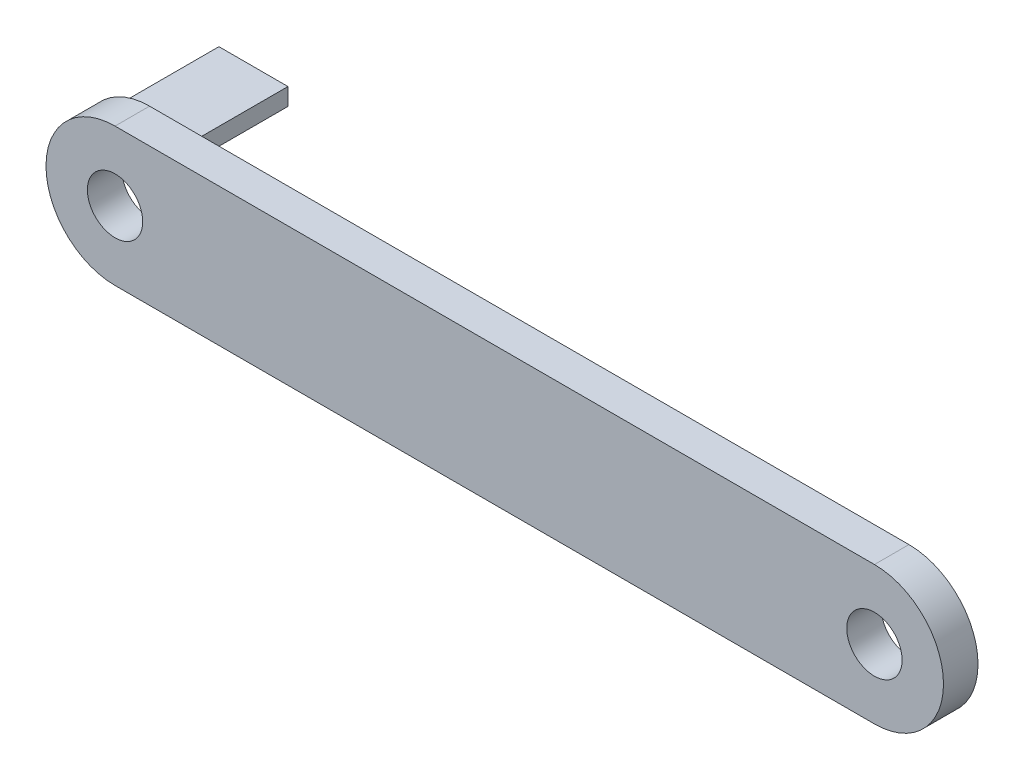
SolidWorks part; units mm, degrees
ref_plane "Front Plane" through (0, 0, 0) normal (0, 0, 1) x (1, 0, 0)
ref_plane "Top Plane" through (0, 0, 0) normal (0, 1, 0) x (1, 0, 0)
ref_plane "Right Plane" through (0, 0, 0) normal (1, 0, 0) x (0, 0, -1)
sketch "Sketch1" plane through (0, 0, 0) normal (0, 0, 1) x (1, 0, 0)
  line L0 (0, 10) -> (110, 10)
  line L1 (0, -10) -> (110, -10)
  circle A0 centre (0, 0) radius 10
  circle A2 centre (0, 0) radius 4.01
  circle A3 centre (110, 0) radius 4.01
  circle A4 centre (110, 0) radius 10
  dimension "D1" = 20
  dimension "D2" = 20
  dimension "D4" = 8.02
  dimension "D5" = 8.02
  dimension "D3" = 110
  dimension "D6" = 110
extrude "Boss-Extrude1" add sketch "Sketch1" along normal blind 5
sketch "Sketch2" plane through (0, 0, 0) normal (0, 0, -1) x (-1, 0, 0)
  circle A2 centre (-20, 0) radius 1.49
  dimension "D1" = 20
  dimension "D2" = 2.98
extrude "Boss-Extrude3" add sketch "Sketch2" along normal blind 4
sketch "Sketch4" plane through (0, 0, 0) normal (0, 0, -1) x (-1, 0, 0)
  line L0 (4.9531, 4.9852) -> (-5.0469, 4.9852)
  line L2 (4.9531, 4.9852) -> (-5.0469, 4.9852)
  line L3 (4.9531, 4.9852) -> (4.9531, 7.4852)
  line L4 (4.9531, 7.4852) -> (-5.0469, 7.4852)
  line L5 (-5.0469, 4.9852) -> (-5.0469, 7.4852)
  dimension "D1" = 2.5
  dimension "D2" = 10
extrude "Boss-Extrude5" add sketch "Sketch4" along normal blind 15 contours L5 L0 L3 L4
